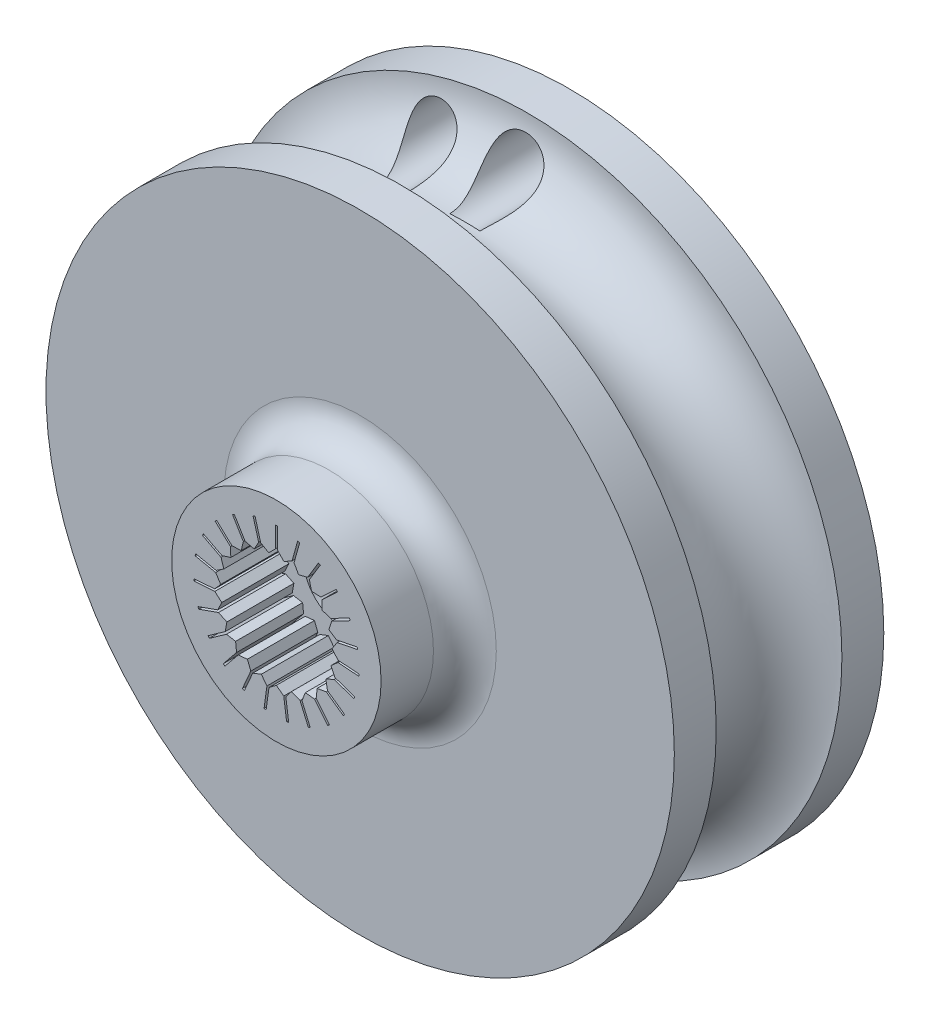
SolidWorks part; units mm, degrees
ref_plane "正面" through (0, 0, 0) normal (0, 0, 1) x (1, 0, 0)
ref_plane "平面" through (0, 0, 0) normal (0, 1, 0) x (1, 0, 0)
ref_plane "右側面" through (0, 0, 0) normal (1, 0, 0) x (0, 0, -1)
sketch "ｽｹｯﾁ8" plane through (0, 0, 0) normal (0, 1, 0) x (1, 0, 0)
  line L0 (0, 0) -> (0, 10)
  line L1 (0, 10) -> (15, 10)
  line L2 (15, 10) -> (15, 8)
  line L3 (0, 0) -> (15, 0)
  line L4 (15, 0) -> (15, 2)
  arc A0 (15, 2) -> (15, 8) centre (15, 5) cw
  dimension "D4" = 3
  dimension "D1" = 15
  dimension "D2" = 2
  dimension "D3" = 10
revolve "回転1" add sketch "ｽｹｯﾁ8" angle 360 about L0
sketch "ｽｹｯﾁ6" plane through (0, 0, 0) normal (0, 0, 1) x (1, 0, 0)
  circle A0 centre (0, 0) radius 5
  dimension "D1" = 10
extrude "ﾎﾞｽ - 押し出し3" add sketch "ｽｹｯﾁ6" along normal blind 4
sketch "ｽｹｯﾁ5" plane through (0, 0, 0) normal (0, 0, 1) x (1, 0, 0)
  line L0 (-0.3625, 2.6375) -> (0, 3) construction
  line L1 (0, 3) -> (0.3625, 2.6375) construction
  line L2 (-0.3625, 2.6375) -> (0, 0) construction
  line L3 (0, 0) -> (0.3625, 2.6375) construction
  line L4 (0, 3) -> (0, 0) construction
  line L5 (-0.05, 2.95) -> (-0.05, 3.95)
  line L6 (-0.05, 3.95) -> (0.05, 3.95)
  line L7 (0.05, 3.95) -> (0.05, 2.95)
  line L8 (-0.05, 2.95) -> (0.05, 2.95) construction
  line L9 (-0.3625, 2.6375) -> (-0.05, 2.95)
  line L10 (-0.05, 2.95) -> (0.05, 2.95) construction
  line L11 (0.3625, 2.6375) -> (0.05, 2.95)
  line L12 (0.3625, 2.6375) -> (0.7478, 2.8541)
  line L13 (0.7478, 2.8541) -> (1.0176, 3.817)
  line L14 (1.1138, 3.79) -> (0.844, 2.8271)
  line L15 (1.0607, 2.4419) -> (0.844, 2.8271)
  line L16 (1.0176, 3.817) -> (1.1138, 3.79)
  line L17 (1.0607, 2.4419) -> (1.4901, 2.5465)
  line L18 (1.4901, 2.5465) -> (2.0096, 3.4009)
  line L19 (2.0951, 3.349) -> (1.5755, 2.4946)
  line L20 (1.6801, 2.0652) -> (1.5755, 2.4946)
  line L21 (2.0096, 3.4009) -> (2.0951, 3.349)
  line L22 (1.6801, 2.0652) -> (2.1218, 2.0501)
  line L23 (2.1218, 2.0501) -> (2.8527, 2.7326)
  line L24 (2.9209, 2.6595) -> (2.1901, 1.977)
  line L25 (2.175, 1.5353) -> (2.1901, 1.977)
  line L26 (2.8527, 2.7326) -> (2.9209, 2.6595)
  line L27 (2.175, 1.5353) -> (2.5963, 1.4016)
  line L28 (2.5963, 1.4016) -> (3.4841, 1.8617)
  line L29 (3.5301, 1.7729) -> (2.6423, 1.3128)
  line L30 (2.5086, 0.8915) -> (2.6423, 1.3128)
  line L31 (3.4841, 1.8617) -> (3.5301, 1.7729)
  line L32 (2.5086, 0.8915) -> (2.8781, 0.6491)
  line L33 (2.8781, 0.6491) -> (3.8572, 0.8526)
  line L34 (3.8776, 0.7547) -> (2.8985, 0.5512)
  line L35 (2.6561, 0.1817) -> (2.8985, 0.5512)
  line L36 (3.8572, 0.8526) -> (3.8776, 0.7547)
  line L37 (2.6561, 0.1817) -> (2.9465, -0.1514)
  line L38 (2.9465, -0.1514) -> (3.9442, -0.2197)
  line L39 (3.9374, -0.3194) -> (2.9397, -0.2512)
  line L40 (2.6066, -0.5417) -> (2.9397, -0.2512)
  line L41 (3.9442, -0.2197) -> (3.9374, -0.3194)
  line L42 (2.6066, -0.5417) -> (2.7964, -0.9408)
  line L43 (2.7964, -0.9408) -> (3.7387, -1.2757)
  line L44 (3.7052, -1.3699) -> (2.7629, -1.035)
  line L45 (2.3638, -1.2248) -> (2.7629, -1.035)
  line L46 (3.7387, -1.2757) -> (3.7052, -1.3699)
  line L47 (2.3638, -1.2248) -> (2.4389, -1.6604)
  line L48 (2.4389, -1.6604) -> (3.2559, -2.237)
  line L49 (3.1982, -2.3187) -> (2.3812, -1.7421)
  line L50 (1.9457, -1.8171) -> (2.3812, -1.7421)
  line L51 (3.2559, -2.237) -> (3.1982, -2.3187)
  line L52 (1.9457, -1.8171) -> (1.9005, -2.2568)
  line L53 (1.9005, -2.2568) -> (2.5316, -3.0325)
  line L54 (2.454, -3.0956) -> (1.8229, -2.3199)
  line L55 (1.3833, -2.2747) -> (1.8229, -2.3199)
  line L56 (2.5316, -3.0325) -> (2.454, -3.0956)
  line L57 (1.3833, -2.2747) -> (1.2211, -2.6859)
  line L58 (1.2211, -2.6859) -> (1.6195, -3.6031)
  line L59 (1.5278, -3.6429) -> (1.1294, -2.7257)
  line L60 (0.7183, -2.5636) -> (1.1294, -2.7257)
  line L61 (1.6195, -3.6031) -> (1.5278, -3.6429)
  line L62 (0.7183, -2.5636) -> (0.4512, -2.9157)
  line L63 (0.4512, -2.9157) -> (0.5874, -3.9064)
  line L64 (0.4883, -3.92) -> (0.3522, -2.9293)
  line L65 (0, -2.6623) -> (0.3522, -2.9293)
  line L66 (0.5874, -3.9064) -> (0.4883, -3.92)
  line L67 (0, -2.6623) -> (-0.3522, -2.9293)
  line L68 (-0.3522, -2.9293) -> (-0.4883, -3.92)
  line L69 (-0.5874, -3.9064) -> (-0.4512, -2.9157)
  line L70 (-0.7183, -2.5636) -> (-0.4512, -2.9157)
  line L71 (-0.4883, -3.92) -> (-0.5874, -3.9064)
  line L72 (-0.7183, -2.5636) -> (-1.1294, -2.7257)
  line L73 (-1.1294, -2.7257) -> (-1.5278, -3.6429)
  line L74 (-1.6195, -3.6031) -> (-1.2211, -2.6859)
  line L75 (-1.3833, -2.2747) -> (-1.2211, -2.6859)
  line L76 (-1.5278, -3.6429) -> (-1.6195, -3.6031)
  line L77 (-1.3833, -2.2747) -> (-1.8229, -2.3199)
  line L78 (-1.8229, -2.3199) -> (-2.454, -3.0956)
  line L79 (-2.5316, -3.0325) -> (-1.9005, -2.2568)
  line L80 (-1.9457, -1.8171) -> (-1.9005, -2.2568)
  line L81 (-2.454, -3.0956) -> (-2.5316, -3.0325)
  line L82 (-1.9457, -1.8171) -> (-2.3812, -1.7421)
  line L83 (-2.3812, -1.7421) -> (-3.1982, -2.3187)
  line L84 (-3.2559, -2.237) -> (-2.4389, -1.6604)
  line L85 (-2.3638, -1.2248) -> (-2.4389, -1.6604)
  line L86 (-3.1982, -2.3187) -> (-3.2559, -2.237)
  line L87 (-2.3638, -1.2248) -> (-2.7629, -1.035)
  line L88 (-2.7629, -1.035) -> (-3.7052, -1.3699)
  line L89 (-3.7387, -1.2757) -> (-2.7964, -0.9408)
  line L90 (-2.6066, -0.5417) -> (-2.7964, -0.9408)
  line L91 (-3.7052, -1.3699) -> (-3.7387, -1.2757)
  line L92 (-2.6066, -0.5417) -> (-2.9397, -0.2512)
  line L93 (-2.9397, -0.2512) -> (-3.9374, -0.3194)
  line L94 (-3.9442, -0.2197) -> (-2.9465, -0.1514)
  line L95 (-2.6561, 0.1817) -> (-2.9465, -0.1514)
  line L96 (-3.9374, -0.3194) -> (-3.9442, -0.2197)
  line L97 (-2.6561, 0.1817) -> (-2.8985, 0.5512)
  line L98 (-2.8985, 0.5512) -> (-3.8776, 0.7547)
  line L99 (-3.8572, 0.8526) -> (-2.8781, 0.6491)
  line L100 (-2.5086, 0.8915) -> (-2.8781, 0.6491)
  line L101 (-3.8776, 0.7547) -> (-3.8572, 0.8526)
  line L102 (-2.5086, 0.8915) -> (-2.6423, 1.3128)
  line L103 (-2.6423, 1.3128) -> (-3.5301, 1.7729)
  line L104 (-3.4841, 1.8617) -> (-2.5963, 1.4016)
  line L105 (-2.175, 1.5353) -> (-2.5963, 1.4016)
  line L106 (-3.5301, 1.7729) -> (-3.4841, 1.8617)
  line L107 (-2.175, 1.5353) -> (-2.1901, 1.977)
  line L108 (-2.1901, 1.977) -> (-2.9209, 2.6595)
  line L109 (-2.8527, 2.7326) -> (-2.1218, 2.0501)
  line L110 (-1.6801, 2.0652) -> (-2.1218, 2.0501)
  line L111 (-2.9209, 2.6595) -> (-2.8527, 2.7326)
  line L112 (-1.6801, 2.0652) -> (-1.5755, 2.4946)
  line L113 (-1.5755, 2.4946) -> (-2.0951, 3.349)
  line L114 (-2.0096, 3.4009) -> (-1.4901, 2.5465)
  line L115 (-1.0607, 2.4419) -> (-1.4901, 2.5465)
  line L116 (-2.0951, 3.349) -> (-2.0096, 3.4009)
  line L117 (-1.0607, 2.4419) -> (-0.844, 2.8271)
  line L118 (-0.844, 2.8271) -> (-1.1138, 3.79)
  line L119 (-1.0176, 3.817) -> (-0.7478, 2.8541)
  line L120 (-0.3625, 2.6375) -> (-0.7478, 2.8541)
  line L121 (-1.1138, 3.79) -> (-1.0176, 3.817)
  circle A0 centre (0, 0) radius 3 construction
  circle A1 centre (0, 0) radius 2.6623 construction
  point P147 (0, 0)
  dimension "D1" = 6
  dimension "D2" = 7.826
  dimension "D3" = 7.826
  dimension "D4" = 0.1
  dimension "D5" = 1
  dimension "D6" = 23
extrude "ｶｯﾄ - 押し出し5" cut sketch "ｽｹｯﾁ5" against normal blind 3.2 from surface at 4 starting at face at (5, 0, 4)
fillet "ﾌｨﾚｯﾄ2" radius 1.5 1 edges at (5, 0, 0)
sketch "ｽｹｯﾁ9" plane through (0, 0, -10) normal (0, 0, -1) x (-1, 0, 0)
  circle A0 centre (0, 0) radius 1.9
  dimension "D1" = 3.8
extrude "ｶｯﾄ - 押し出し6" cut sketch "ｽｹｯﾁ9" against normal through all
sketch "ｽｹｯﾁ10" plane through (0, 0, -10) normal (0, 0, -1) x (-1, 0, 0)
  circle A0 centre (0, 0) radius 3
  dimension "D1" = 6
extrude "ｶｯﾄ - 押し出し7" cut sketch "ｽｹｯﾁ10" against normal offset from surface (5.8 mm away) 5 up to face at (1.9, 0, 0.8)
sketch "ｽｹｯﾁ11" plane through (0, 0, -10) normal (0, 0, 1) x (1, 0, 0)
  circle A0 centre (0, 0) radius 13 construction
  circle A1 centre (0, 13) radius 1.25
  circle A2 centre (-3.9524, 12.3846) radius 1.25
  dimension "D1" = 2.5
  dimension "D2" = 26
  dimension "D3" = 4
extrude "ｶｯﾄ - 押し出し8" cut sketch "ｽｹｯﾁ11" along normal blind 5 contours A1 | A2
equation "\"18.4.300mm\"= 18.3"
equation "\"D2@ｽｹｯﾁ5\"=360deg/46"
equation "\"D3@ｽｹｯﾁ5\"=\"D2@ｽｹｯﾁ5\""
